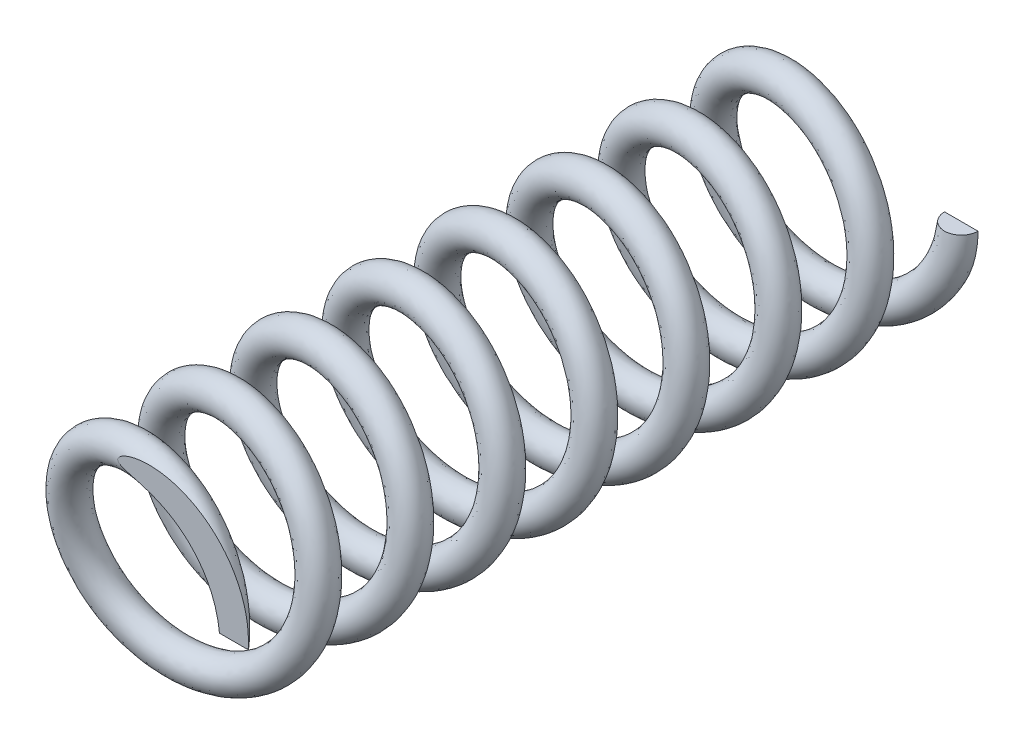
SolidWorks part; units mm, degrees
ref_plane "前视基准面" through (0, 0, 0) normal (0, 0, 1) x (1, 0, 0)
ref_plane "上视基准面" through (0, 0, 0) normal (0, 1, 0) x (1, 0, 0)
ref_plane "右视基准面" through (0, 0, 0) normal (1, 0, 0) x (0, 0, -1)
sketch "草图1" plane through (0, 0, 0) normal (0, 0, 1) x (1, 0, 0)
  circle A0 centre (0, 0) radius 3
  dimension "D1" = 6
curve "螺旋线/涡状线1" pitch 2.75 height 22 turns 8
sketch "草图2" plane through (0, 0, 0) normal (0, 1, 0) x (1, 0, 0)
  circle A0 centre (3, 0) radius 0.5
  spline S0 degree 3 poles (3, 0) (3, -0.0569) (2.8438, -0.172) (2.1765, -0.3437) (1.1779, -0.5156) (0, -0.6875) (-1.1779, -0.8594) (-2.1765, -1.0312) (-2.8438, -1.2031) (-3.0781, -1.375) (-2.8438, -1.5469) (-2.1765, -1.7187) (-0.8451, -1.9479) (0.8451, -2.1771) (2.1765, -2.4062) (2.8438, -2.5781) (3.0781, -2.75) (2.8438, -2.9219) (2.1765, -3.0937) (0.8451, -3.3229) (-0.8451, -3.5521) (-2.1765, -3.7812) (-2.8438, -3.9531) (-3.0781, -4.125) (-2.8438, -4.2969) (-2.1765, -4.4688) (-0.8451, -4.6979) (0.8451, -4.9271) (2.1765, -5.1563) (2.8438, -5.3281) (3.0781, -5.5) (2.8438, -5.6719) (2.1765, -5.8438) (0.8451, -6.0729) (-0.8451, -6.3021) (-2.1765, -6.5313) (-2.8438, -6.7031) (-3.0781, -6.875) (-2.8438, -7.0469) (-2.1765, -7.2188) (-0.8451, -7.4479) (0.8451, -7.6771) (2.1765, -7.9063) (2.8438, -8.0781) (3.0781, -8.25) (2.8438, -8.4219) (2.1765, -8.5938) (0.8451, -8.8229) (-0.8451, -9.0521) (-2.1765, -9.2813) (-2.8438, -9.4531) (-3.0781, -9.625) (-2.8438, -9.7969) (-2.1765, -9.9688) (-0.8451, -10.1979) (0.8451, -10.4271) (2.1765, -10.6563) (2.8438, -10.8281) (3.0781, -11) (2.8438, -11.1719) (2.1765, -11.3438) (0.8451, -11.5729) (-0.8451, -11.8021) (-2.1765, -12.0313) (-2.8438, -12.2031) (-3.0781, -12.375) (-2.8438, -12.5469) (-2.1765, -12.7188) (-0.8451, -12.9479) (0.8451, -13.1771) (2.1765, -13.4063) (2.8438, -13.5781) (3.0781, -13.75) (2.8438, -13.9219) (2.1765, -14.0938) (0.8451, -14.3229) (-0.8451, -14.5521) (-2.1765, -14.7813) (-2.8438, -14.9531) (-3.0781, -15.125) (-2.8438, -15.2969) (-2.1765, -15.4688) (-0.8451, -15.6979) (0.8451, -15.9271) (2.1765, -16.1563) (2.8438, -16.3281) (3.0781, -16.5) (2.8438, -16.6719) (2.1765, -16.8437) (0.8451, -17.0729) (-0.8451, -17.3021) (-2.1765, -17.5312) (-2.8438, -17.7031) (-3.0781, -17.875) (-2.8438, -18.0469) (-2.1765, -18.2187) (-0.8451, -18.4479) (0.8451, -18.6771) (2.1765, -18.9063) (2.8438, -19.0781) (3.0781, -19.25) (2.8438, -19.4219) (2.1765, -19.5938) (0.8451, -19.8229) (-0.8451, -20.0521) (-2.1765, -20.2813) (-2.8438, -20.4531) (-3.0781, -20.625) (-2.8438, -20.7969) (-2.1765, -20.9688) (-1.1779, -21.1406) (0, -21.3125) (1.1779, -21.4844) (2.1765, -21.6563) (2.8438, -21.828) (3, -21.9431) (3, -22) knots 0 0 0 0 0.007813 0.015625 0.023438 0.03125 0.039063 0.046875 0.054688 0.0625 0.070313 0.078125 0.085938 0.101563 0.109375 0.117188 0.125 0.132813 0.140625 0.148438 0.164063 0.171875 0.179688 0.1875 0.195313 0.203125 0.210938 0.226563 0.234375 0.242188 0.25 0.257813 0.265625 0.273438 0.289063 0.296875 0.304688 0.3125 0.320313 0.328125 0.335938 0.351563 0.359375 0.367188 0.375 0.382813 0.390625 0.398438 0.414063 0.421875 0.429688 0.4375 0.445313 0.453125 0.460938 0.476563 0.484375 0.492188 0.5 0.507813 0.515625 0.523438 0.539063 0.546875 0.554688 0.5625 0.570313 0.578125 0.585938 0.601563 0.609375 0.617188 0.625 0.632813 0.640625 0.648438 0.664063 0.671875 0.679688 0.6875 0.695313 0.703125 0.710938 0.726563 0.734375 0.742188 0.75 0.757813 0.765625 0.773438 0.789063 0.796875 0.804688 0.8125 0.820313 0.828125 0.835938 0.851563 0.859375 0.867188 0.875 0.882813 0.890625 0.898438 0.914063 0.921875 0.929688 0.9375 0.945313 0.953125 0.960938 0.96875 0.976563 0.984375 0.992188 1 1 1 1 construction
  dimension "D1" = 1
sweep "扫描1" add profiles "草图2" path "螺旋线/涡状线1"
sketch "草图3" plane through (0, 0, 0) normal (0, 1, 0) x (1, 0, 0)
  line L0 (2.4968, -21.7428) -> (-7.086, -21.7428)
  line L1 (2.4968, -21.7428) -> (4.8848, -21.7428)
  line L2 (4.8848, -21.7428) -> (4.8848, -25.5509)
  line L3 (4.8848, -25.5509) -> (-7.086, -25.5509)
  line L4 (-7.086, -25.5509) -> (-7.086, -21.7428)
  line L5 (5.52, 0) -> (-4.8056, 0)
  line L6 (-4.8056, 0) -> (-4.8056, 1.0494)
  line L7 (-4.8056, 1.0494) -> (5.52, 1.0494)
  line L8 (5.52, 1.0494) -> (5.52, 0)
  spline S1 degree 3 poles (3, 0) (3, -0.0569) (2.8438, -0.172) (2.1765, -0.3437) (1.1779, -0.5156) (0, -0.6875) (-1.1779, -0.8594) (-2.1765, -1.0312) (-2.8438, -1.2031) (-3.0781, -1.375) (-2.8438, -1.5469) (-2.1765, -1.7187) (-0.8451, -1.9479) (0.8451, -2.1771) (2.1765, -2.4062) (2.8438, -2.5781) (3.0781, -2.75) (2.8438, -2.9219) (2.1765, -3.0937) (0.8451, -3.3229) (-0.8451, -3.5521) (-2.1765, -3.7812) (-2.8438, -3.9531) (-3.0781, -4.125) (-2.8438, -4.2969) (-2.1765, -4.4688) (-0.8451, -4.6979) (0.8451, -4.9271) (2.1765, -5.1563) (2.8438, -5.3281) (3.0781, -5.5) (2.8438, -5.6719) (2.1765, -5.8438) (0.8451, -6.0729) (-0.8451, -6.3021) (-2.1765, -6.5313) (-2.8438, -6.7031) (-3.0781, -6.875) (-2.8438, -7.0469) (-2.1765, -7.2188) (-0.8451, -7.4479) (0.8451, -7.6771) (2.1765, -7.9063) (2.8438, -8.0781) (3.0781, -8.25) (2.8438, -8.4219) (2.1765, -8.5938) (0.8451, -8.8229) (-0.8451, -9.0521) (-2.1765, -9.2813) (-2.8438, -9.4531) (-3.0781, -9.625) (-2.8438, -9.7969) (-2.1765, -9.9688) (-0.8451, -10.1979) (0.8451, -10.4271) (2.1765, -10.6563) (2.8438, -10.8281) (3.0781, -11) (2.8438, -11.1719) (2.1765, -11.3438) (0.8451, -11.5729) (-0.8451, -11.8021) (-2.1765, -12.0313) (-2.8438, -12.2031) (-3.0781, -12.375) (-2.8438, -12.5469) (-2.1765, -12.7188) (-0.8451, -12.9479) (0.8451, -13.1771) (2.1765, -13.4063) (2.8438, -13.5781) (3.0781, -13.75) (2.8438, -13.9219) (2.1765, -14.0938) (0.8451, -14.3229) (-0.8451, -14.5521) (-2.1765, -14.7813) (-2.8438, -14.9531) (-3.0781, -15.125) (-2.8438, -15.2969) (-2.1765, -15.4688) (-0.8451, -15.6979) (0.8451, -15.9271) (2.1765, -16.1563) (2.8438, -16.3281) (3.0781, -16.5) (2.8438, -16.6719) (2.1765, -16.8437) (0.8451, -17.0729) (-0.8451, -17.3021) (-2.1765, -17.5312) (-2.8438, -17.7031) (-3.0781, -17.875) (-2.8438, -18.0469) (-2.1765, -18.2187) (-0.8451, -18.4479) (0.8451, -18.6771) (2.1765, -18.9063) (2.8438, -19.0781) (3.0781, -19.25) (2.8438, -19.4219) (2.1765, -19.5938) (0.8451, -19.8229) (-0.8451, -20.0521) (-2.1765, -20.2813) (-2.8438, -20.4531) (-3.0781, -20.625) (-2.8438, -20.7969) (-2.1765, -20.9688) (-1.1779, -21.1406) (0, -21.3125) (1.1779, -21.4844) (2.1765, -21.6563) (2.8438, -21.828) (3, -21.9431) (3, -22) knots 0 0 0 0 0.007813 0.015625 0.023438 0.03125 0.039063 0.046875 0.054688 0.0625 0.070313 0.078125 0.085938 0.101563 0.109375 0.117188 0.125 0.132813 0.140625 0.148438 0.164063 0.171875 0.179688 0.1875 0.195313 0.203125 0.210938 0.226563 0.234375 0.242188 0.25 0.257813 0.265625 0.273438 0.289063 0.296875 0.304688 0.3125 0.320313 0.328125 0.335938 0.351563 0.359375 0.367188 0.375 0.382813 0.390625 0.398438 0.414063 0.421875 0.429688 0.4375 0.445313 0.453125 0.460938 0.476563 0.484375 0.492188 0.5 0.507813 0.515625 0.523438 0.539063 0.546875 0.554688 0.5625 0.570313 0.578125 0.585938 0.601563 0.609375 0.617188 0.625 0.632813 0.640625 0.648438 0.664063 0.671875 0.679688 0.6875 0.695313 0.703125 0.710938 0.726563 0.734375 0.742188 0.75 0.757813 0.765625 0.773438 0.789063 0.796875 0.804688 0.8125 0.820313 0.828125 0.835938 0.851563 0.859375 0.867188 0.875 0.882813 0.890625 0.898438 0.914063 0.921875 0.929688 0.9375 0.945313 0.953125 0.960938 0.96875 0.976563 0.984375 0.992188 1 1 1 1 construction
extrude "切除-拉伸1" cut sketch "草图3" against normal through all both and the other way through all
sketch "草图4" plane through (0, 0, 0) normal (0, 1, 0) x (1, 0, 0)
  line L0 (0, 0) -> (0, -22.7779)
